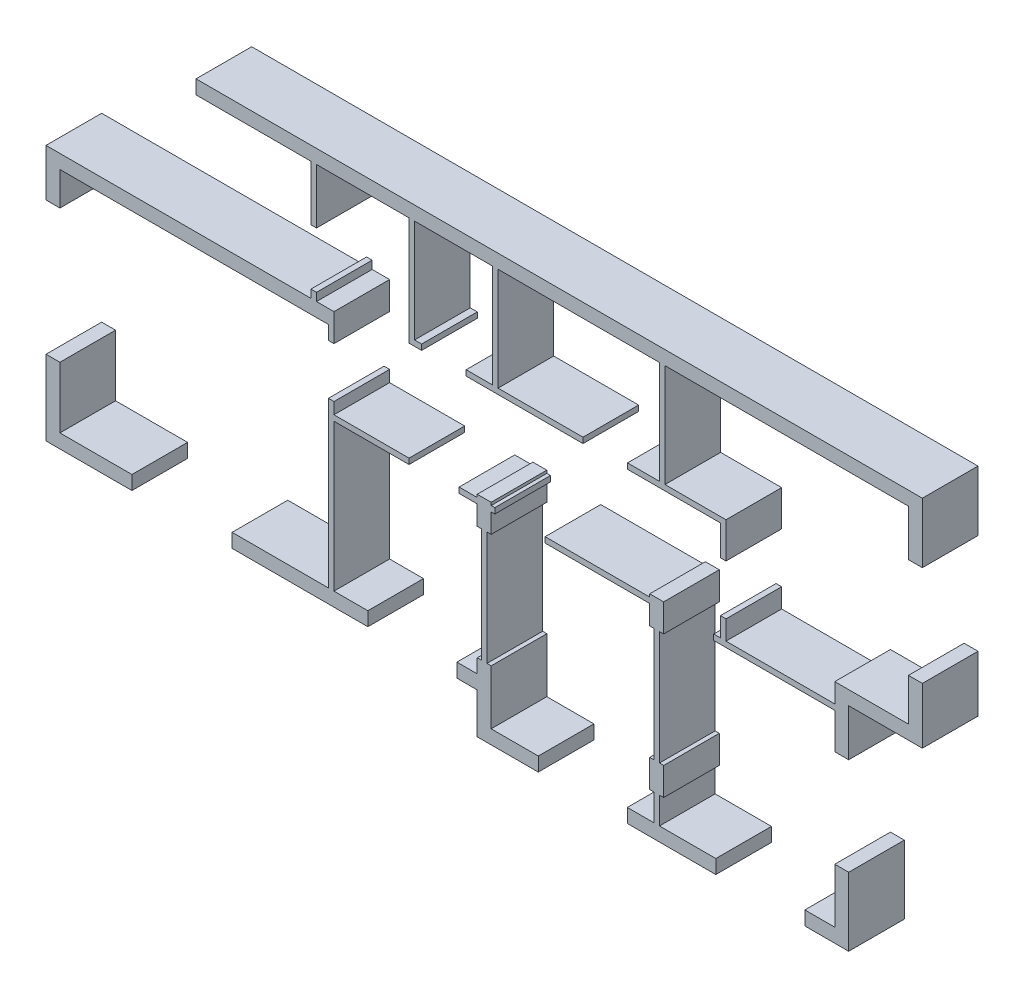
SolidWorks part; units mm, degrees
ref_plane "Front Plane" through (0, 0, 0) normal (0, 0, 1) x (1, 0, 0)
ref_plane "Top Plane" through (0, 0, 0) normal (0, 1, 0) x (1, 0, 0)
ref_plane "Right Plane" through (0, 0, 0) normal (1, 0, 0) x (0, 0, -1)
sketch "Sketch2" plane through (0, 0, 0) normal (0, 0, 1) x (1, 0, 0)
  line L0 (50, 39.7629) -> (50, 43.5) construction
  line L1 (50, 43.5) -> (0, 43.5) construction
  line L2 (0, 43.5) -> (0, 36.2461) construction
  line L3 (0, 0) -> (14.1944, 0) construction
  line L4 (50, 0) -> (50, 29.2835) construction
  line L5 (49.5, 42.25) -> (48.75, 42.25)
  line L6 (50.5, 44.75) -> (47.3643, 44.75)
  line L7 (-1.25, 44.75) -> (-1.25, 36.2461)
  line L8 (-1.25, -1.25) -> (14.1944, -1.25)
  line L9 (49.5, 39.7629) -> (50.5, 39.7629)
  line L10 (48.75, 42.25) -> (1.25, 42.25)
  line L11 (1.25, 42.25) -> (1.25, 36.2461)
  line L12 (1.25, 1.25) -> (14.1944, 1.25)
  line L13 (50.5, 1.25) -> (50.5, 27.6974)
  line L14 (49.5, 1.25) -> (49.5, 29.2835)
  line L15 (49.5, 0) -> (49.5, 29.2835) construction
  line L16 (50, 0) -> (56.5905, 0) construction
  line L17 (50, -1.25) -> (56.5905, -1.25)
  line L18 (50.5, 1.25) -> (56.5905, 1.25)
  line L19 (77.5, 0) -> (77.5, -7.3026) construction
  line L20 (76.25, -1.25) -> (76.25, -7.3026)
  line L21 (78.75, 0) -> (78.75, -6.0526)
  line L22 (76.25, 0) -> (76.25, -7.3026) construction
  line L23 (50, -1.25) -> (77.5, -1.25) construction
  line L24 (77.5, -7.3026) -> (87.2177, -7.3026) construction
  line L25 (77.5, -8.5526) -> (87.2177, -8.5526)
  line L26 (78.75, -6.0526) -> (87.2177, -6.0526)
  line L27 (77.5, -6.0526) -> (108.5, -6.0526) construction
  line L28 (78.75, 0) -> (78.75, -7.3026) construction
  line L29 (76.25, -7.3026) -> (76.25, -8.5526)
  line L30 (76.25, -8.5526) -> (77.5, -8.5526)
  line L31 (50, 28.1974) -> (63.9905, 28.1974) construction
  line L32 (77.5, 28.1974) -> (77.5, 0) construction
  line L33 (50.5, 27.6974) -> (63.9905, 27.6974)
  line L34 (77, 24.2066) -> (77, 3.75)
  line L35 (50.5, 28.6974) -> (63.9905, 28.6974)
  line L36 (78, 24.2066) -> (78, 3.75)
  line L37 (50, 28.6974) -> (78, 28.6974) construction
  line L38 (50, 27.6974) -> (77, 27.6974) construction
  line L39 (77, 27.6974) -> (77, 0) construction
  line L40 (50, 1.25) -> (77.5, 1.25) construction
  line L41 (50.5, 0) -> (50.5, 29.2835) construction
  line L42 (108.5, -7.3026) -> (108.5, 28.1974) construction
  line L43 (109, -6.0526) -> (109, -1.25)
  line L44 (108, -6.0526) -> (108, -1.25)
  line L45 (108.5, 28.1974) -> (88.4429, 28.1974) construction
  line L46 (77.5, 28.1974) -> (79.4017, 28.1974) construction
  line L47 (107.25, 28.6974) -> (88.4429, 28.6974)
  line L48 (78.75, 27.6974) -> (79.4017, 27.6974)
  line L49 (107.25, 27.6974) -> (88.4429, 27.6974)
  line L50 (78.75, 28.6974) -> (78.75, 29.2066)
  line L51 (78, 28.6974) -> (78, 0) construction
  line L52 (77.5, 27.6974) -> (79.4017, 27.6974) construction
  line L53 (108.5, 27.6974) -> (88.4429, 27.6974) construction
  line L54 (108, -7.3026) -> (108, 28.1974) construction
  line L55 (107.25, 28.6974) -> (107.25, 29.2066)
  line L56 (109, 24.2066) -> (109.75, 24.2066)
  line L57 (108.5, -7.3026) -> (119.121, -7.3026) construction
  line L58 (141.75, -7.3026) -> (141.75, 3.75) construction
  line L59 (108.5, -8.5526) -> (119.121, -8.5526)
  line L60 (143, -8.5526) -> (143, 3.75)
  line L61 (109, -6.0526) -> (119.121, -6.0526)
  line L62 (140.5, -6.0526) -> (140.5, 3.75)
  line L63 (141.75, 30.919) -> (154.9905, 30.919) construction
  line L64 (154.9905, 30.919) -> (154.9905, 39.7629) construction
  line L65 (141.75, 28.1974) -> (118.75, 28.1974) construction
  line L66 (140.5, 28.6974) -> (120.9533, 28.6974)
  line L67 (140.5, 27.6974) -> (118.75, 27.6974)
  line L68 (141.75, 28.6974) -> (118.75, 28.6974) construction
  line L69 (141.75, 27.6974) -> (118.75, 27.6974) construction
  line L70 (143, 29.669) -> (156.2405, 29.669)
  line L71 (156.2405, 29.669) -> (156.2405, 39.7629)
  line L72 (141.75, 32.169) -> (153.7405, 32.169)
  line L73 (153.7405, 32.169) -> (153.7405, 39.7629)
  line L74 (141.75, 29.669) -> (156.2405, 29.669) construction
  line L75 (141.75, 32.169) -> (140.5, 32.169)
  line L76 (140.5, 32.169) -> (140.5, 30.919)
  line L77 (154.9905, 67.3376) -> (25.7126, 67.3376) construction
  line L78 (154.9905, 68.5876) -> (25.7126, 68.5876)
  line L79 (153.7405, 66.0876) -> (109.9905, 66.0876)
  line L80 (153.7405, 32.169) -> (153.7405, 67.3376) construction
  line L81 (154.9905, 66.0876) -> (25.7126, 66.0876) construction
  line L82 (154.9905, 68.5876) -> (156.2405, 68.5876)
  line L83 (156.2405, 68.5876) -> (156.2405, 67.3376)
  line L84 (109, -7.3026) -> (109, 28.1974) construction
  line L85 (108.5, -6.0526) -> (140.5, -6.0526) construction
  line L86 (140.5, 28.6974) -> (140.5, 30.919)
  line L87 (140.5, -6.0526) -> (140.5, 30.919) construction
  line L88 (143, -8.5526) -> (143, 30.919) construction
  line L89 (109.4905, 67.3376) -> (109.4905, 47.0876) construction
  line L90 (79.4905, 67.3376) -> (79.4905, 47.0876) construction
  line L91 (64.4905, 67.3376) -> (64.4905, 47.0876) construction
  line L92 (116.9905, 47.0876) -> (103.2529, 47.0876) construction
  line L93 (63.9905, 66.0876) -> (63.9905, 46.5876)
  line L94 (116.9905, 47.5876) -> (117.4905, 47.5876)
  line L95 (78.9905, 66.0876) -> (78.9905, 47.5876)
  line L96 (108.9905, 66.0876) -> (108.9905, 47.5876)
  line L97 (64.9905, 66.0876) -> (64.9905, 47.5876)
  line L98 (116.9905, 47.5876) -> (109.9905, 47.5876)
  line L99 (79.9905, 66.0876) -> (79.9905, 47.5876)
  line L100 (109.9905, 66.0876) -> (109.9905, 47.5876)
  line L101 (109.9905, 67.3376) -> (109.9905, 47.0876) construction
  line L102 (108.9905, 67.3376) -> (108.9905, 47.0876) construction
  line L103 (79.9905, 67.3376) -> (79.9905, 47.0876) construction
  line L104 (78.9905, 67.3376) -> (78.9905, 47.0876) construction
  line L105 (78.9905, 66.0876) -> (64.9905, 66.0876)
  line L106 (108.9905, 66.0876) -> (79.9905, 66.0876)
  line L107 (64.9905, 67.3376) -> (64.9905, 47.5876) construction
  line L108 (63.9905, 67.3376) -> (63.9905, 46.5876) construction
  line L109 (63.9905, 66.0876) -> (47.3643, 66.0876)
  line L110 (78.9905, 47.5876) -> (74.2528, 47.5876)
  line L111 (155.3404, 47.5876) -> (64.9905, 47.5876) construction
  line L112 (108.9905, 47.5876) -> (103.2529, 47.5876)
  line L113 (76.25, 3.75) -> (77, 3.75)
  line L114 (78.75, 3.75) -> (78.75, -0.8827)
  line L115 (76.25, 1.25) -> (76.25, 3.75)
  line L116 (78, 3.75) -> (78.75, 3.75)
  line L117 (1.25, 1.25) -> (50, 1.25) construction
  line L118 (155.3404, 46.5876) -> (63.9905, 46.5876) construction
  line L119 (107.25, 3.75) -> (108, 3.75)
  line L120 (107.25, -1.25) -> (108, -1.25)
  line L121 (109.75, 3.75) -> (109.75, -1.25)
  line L122 (107.25, 3.75) -> (107.25, -1.25)
  line L123 (109, 3.75) -> (109, 24.2066)
  line L124 (108, 3.75) -> (108, 24.2066)
  line L125 (109, 3.75) -> (109.75, 3.75)
  line L126 (109, -1.25) -> (109.75, -1.25)
  line L127 (78.75, 29.2066) -> (76.25, 29.2066)
  line L128 (109.75, 29.2066) -> (107.25, 29.2066)
  line L129 (107.25, 24.2066) -> (108, 24.2066)
  line L130 (78.75, 24.2066) -> (78, 24.2066)
  line L131 (107.25, 24.2066) -> (107.25, 27.6974)
  line L132 (109.75, 24.2066) -> (109.75, 29.2066)
  line L133 (108.5, 28.6974) -> (88.4429, 28.6974) construction
  line L134 (76.25, 24.2066) -> (76.25, 27.6974)
  line L135 (78.75, 24.2066) -> (78.75, 27.6974)
  line L136 (78.75, 28.6974) -> (79.4017, 28.6974)
  line L137 (77, 24.2066) -> (76.25, 24.2066)
  line L138 (76.25, 28.6974) -> (76.25, 29.2066)
  line L139 (153.7405, 57.7629) -> (153.7405, 66.0876)
  line L140 (49.5, 39.7629) -> (49.5, 42.25)
  line L141 (50.5, 28.6974) -> (50.5, 30.7629)
  line L142 (50.5, 30.7629) -> (49.5, 30.7629)
  line L143 (49.5, 30.7629) -> (49.5, 29.2835)
  line L144 (50.5, 39.7629) -> (50.5, 42.25)
  line L145 (50.5, 42.25) -> (50.5, 44.75)
  line L146 (51.25, 44.75) -> (-1.25, 44.75) construction
  line L147 (51.25, 39.6957) -> (51.25, 44.75) construction
  line L148 (48.75, 39.6957) -> (48.75, 42.25) construction
  line L149 (50, 39.6957) -> (50, 43.5) construction
  line L150 (25.7126, 68.5876) -> (25.7126, 66.0876)
  line L151 (79.4017, 28.6974) -> (79.4017, 27.6974)
  line L152 (88.4429, 28.6974) -> (88.4429, 27.6974)
  line L153 (72.9905, 28.6974) -> (72.9905, 27.6974)
  line L154 (63.9905, 28.6974) -> (63.9905, 27.6974)
  line L155 (72.9905, 28.6974) -> (76.25, 28.6974)
  line L156 (72.9905, 28.1974) -> (77.5, 28.1974) construction
  line L157 (50, 28.1974) -> (77.5, 28.1974) construction
  line L158 (72.9905, 27.6974) -> (76.25, 27.6974)
  line L159 (116.9905, 47.0876) -> (116.9905, 47.5876) construction
  line L163 (116.4905, 46.5876) -> (119.9533, 46.5876)
  line L164 (119.9533, 46.5876) -> (119.9533, 41.1631)
  line L165 (117.4905, 47.5876) -> (120.9533, 47.5876)
  line L166 (116.4905, 46.5876) -> (103.2529, 46.5876)
  line L167 (155.3404, 47.0876) -> (64.4905, 47.0876) construction
  line L169 (118.75, 28.6974) -> (118.75, 27.6974)
  line L170 (120.4533, 28.1974) -> (120.4533, 29.2066) construction
  line L171 (120.9533, 28.6974) -> (120.9533, 32.1631)
  line L172 (119.9533, 28.6974) -> (119.9533, 32.1631)
  line L173 (119.9533, 32.1631) -> (120.9533, 32.1631)
  line L174 (119.9533, 28.1974) -> (119.9533, 32.1631) construction
  line L175 (119.9533, 28.6974) -> (118.75, 28.6974)
  line L176 (120.9533, 28.1974) -> (120.9533, 32.1631) construction
  line L177 (120.4533, 28.1974) -> (120.4533, 32.1631) construction
  line L178 (-1.25, 36.2461) -> (1.25, 36.2461)
  line L179 (-1.25, 12.2461) -> (1.25, 12.2461)
  line L180 (14.1944, 1.25) -> (14.1944, -1.25)
  line L181 (32.1944, 1.25) -> (32.1944, -1.25)
  line L182 (56.5905, 1.25) -> (56.5905, -1.25)
  line L183 (72.5905, 1.25) -> (72.5905, -1.25)
  line L184 (87.2177, -6.0526) -> (87.2177, -8.5526)
  line L185 (103.2177, -6.0526) -> (103.2177, -8.5526)
  line L186 (119.121, -6.0526) -> (119.121, -8.5526)
  line L187 (135.121, -6.0526) -> (135.121, -8.5526)
  line L188 (140.5, 3.75) -> (143, 3.75)
  line L189 (140.5, 21.25) -> (143, 21.25)
  line L190 (153.7405, 39.7629) -> (156.2405, 39.7629)
  line L191 (153.7405, 57.7629) -> (156.2405, 57.7629)
  line L192 (-1.25, 12.2461) -> (-1.25, -1.25)
  line L193 (-1.25, 44.75) -> (-1.25, -1.25) construction
  line L194 (0, 12.2461) -> (0, 0) construction
  line L195 (0, 43.5) -> (0, 0) construction
  line L196 (1.25, 12.2461) -> (1.25, 1.25)
  line L197 (1.25, 42.25) -> (1.25, 1.25) construction
  line L198 (32.1944, 1.25) -> (49.5, 1.25)
  line L199 (32.1944, 0) -> (50, 0) construction
  line L200 (0, 0) -> (50, 0) construction
  line L201 (32.1944, -1.25) -> (50, -1.25)
  line L202 (-1.25, -1.25) -> (50, -1.25) construction
  line L203 (72.5905, 1.25) -> (77, 1.25)
  line L204 (72.5905, 0) -> (77.5, 0) construction
  line L205 (50, 0) -> (77.5, 0) construction
  line L206 (72.5905, -1.25) -> (76.25, -1.25)
  line L207 (103.2177, -6.0526) -> (108, -6.0526)
  line L208 (103.2177, -7.3026) -> (108.5, -7.3026) construction
  line L209 (77.5, -7.3026) -> (108.5, -7.3026) construction
  line L210 (103.2177, -8.5526) -> (108.5, -8.5526)
  line L211 (77.5, -8.5526) -> (108.5, -8.5526) construction
  line L212 (135.121, -6.0526) -> (140.5, -6.0526)
  line L213 (135.121, -7.3026) -> (141.75, -7.3026) construction
  line L214 (108.5, -7.3026) -> (141.75, -7.3026) construction
  line L215 (135.121, -8.5526) -> (143, -8.5526)
  line L216 (108.5, -8.5526) -> (143, -8.5526) construction
  line L217 (140.5, 21.25) -> (140.5, 27.6974)
  line L218 (141.75, 21.25) -> (141.75, 30.919) construction
  line L219 (141.75, -7.3026) -> (141.75, 30.919) construction
  line L220 (143, 21.25) -> (143, 29.669)
  line L221 (154.9905, 57.7629) -> (154.9905, 67.3376) construction
  line L222 (154.9905, 30.919) -> (154.9905, 67.3376) construction
  line L223 (156.2405, 57.7629) -> (156.2405, 67.3376)
  line L224 (156.2405, 29.669) -> (156.2405, 67.3376) construction
  line L225 (66.2528, 47.5876) -> (66.2528, 46.5876)
  line L226 (74.2528, 47.5876) -> (74.2528, 46.5876)
  line L227 (95.2529, 47.5876) -> (95.2529, 46.5876)
  line L228 (103.2529, 47.5876) -> (103.2529, 46.5876)
  line L229 (66.2528, 47.5876) -> (64.9905, 47.5876)
  line L230 (66.2528, 47.0876) -> (64.4905, 47.0876) construction
  line L231 (66.2528, 46.5876) -> (63.9905, 46.5876)
  line L232 (95.2529, 47.5876) -> (79.9905, 47.5876)
  line L233 (95.2529, 47.0876) -> (74.2528, 47.0876) construction
  line L234 (95.2529, 46.5876) -> (74.2528, 46.5876)
  line L235 (46.3643, 44.75) -> (46.3643, 46.1952)
  line L237 (47.3643, 66.0876) -> (47.3643, 56.1952)
  line L238 (46.3643, 44.75) -> (-1.25, 44.75)
  line L239 (120.9533, 47.5876) -> (120.9533, 41.1631)
  line L240 (119.9533, 41.1631) -> (120.9533, 41.1631)
  line L241 (46.3643, 56.1952) -> (47.3643, 56.1952)
  line L242 (46.3643, 46.1952) -> (47.3643, 46.1952)
  line L243 (46.3643, 56.1952) -> (46.3643, 66.0876)
  line L244 (47.3643, 46.1952) -> (47.3643, 44.75)
  line L245 (46.3643, 66.0876) -> (25.7126, 66.0876)
  dimension "D28" = 9
  dimension "D1" = 50
  dimension "D2" = 43.5
  dimension "D3" = 27.5
  dimension "D4" = 31
  dimension "D5" = 33.25
  dimension "D6" = 35.5
  dimension "D7" = 45.5
  dimension "D8" = 30
  dimension "D9" = 15
  dimension "D10" = 19
  dimension "D11" = 5
  dimension "D12" = 5
  dimension "D13" = 1
  dimension "D14" = 24
  dimension "D15" = 18
  dimension "D16" = 16
  dimension "D17" = 16
  dimension "D18" = 16
  dimension "D19" = 17.5
  dimension "D20" = 18
  dimension "D21" = 8
  dimension "D22" = 8
  dimension "D23" = 9
  dimension "D24" = 9
  dimension "D25" = 9
  dimension "D26" = 10
  dimension "D29" = 9.0412
extrude "Boss-Extrude1" add sketch "Sketch2" along normal blind 10
